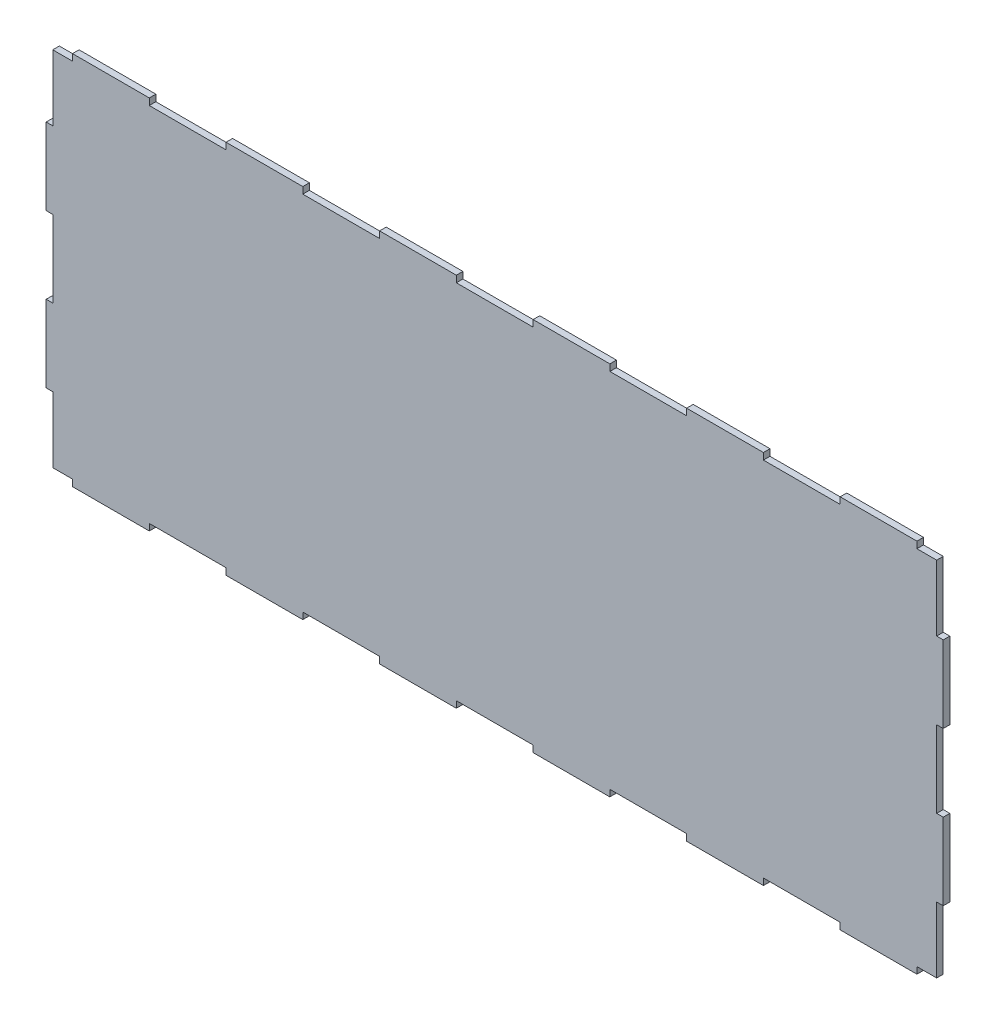
SolidWorks part; units mm, degrees
ref_plane "Front Plane" through (0, 0, 0) normal (0, 0, 1) x (1, 0, 0)
ref_plane "Top Plane" through (0, 0, 0) normal (0, 1, 0) x (1, 0, 0)
ref_plane "Right Plane" through (0, 0, 0) normal (1, 0, 0) x (0, 0, -1)
sketch "Model" plane through (0, 0, 0) normal (0, 0, 1) x (1, 0, 0)
  line L0 (192.5, 85.5) -> (157.5, 85.5)
  line L1 (157.5, 85.5) -> (157.5, 82.5)
  line L2 (157.5, 82.5) -> (122.5, 82.5)
  line L3 (122.5, 82.5) -> (122.5, 85.5)
  line L4 (122.5, 85.5) -> (87.5, 85.5)
  line L5 (87.5, 85.5) -> (87.5, 82.5)
  line L6 (87.5, 82.5) -> (52.5, 82.5)
  line L7 (52.5, 82.5) -> (52.5, 85.5)
  line L8 (52.5, 85.5) -> (17.5, 85.5)
  line L9 (17.5, 85.5) -> (17.5, 82.5)
  line L10 (17.5, 82.5) -> (-17.5, 82.5)
  line L11 (-17.5, 82.5) -> (-17.5, 85.5)
  line L12 (-17.5, 85.5) -> (-52.5, 85.5)
  line L13 (-52.5, 85.5) -> (-52.5, 82.5)
  line L14 (-52.5, 82.5) -> (-87.5, 82.5)
  line L15 (-87.5, 82.5) -> (-87.5, 85.5)
  line L16 (-87.5, 85.5) -> (-122.5, 85.5)
  line L17 (-122.5, 85.5) -> (-122.5, 82.5)
  line L18 (-122.5, 82.5) -> (-157.5, 82.5)
  line L19 (-157.5, 82.5) -> (-157.5, 85.5)
  line L20 (-157.5, 85.5) -> (-192.5, 85.5)
  line L21 (-192.5, 85.5) -> (-192.5, 82.5)
  line L22 (-192.5, 82.5) -> (-201.5, 82.5)
  line L23 (-201.5, 82.5) -> (-201.5, 52.5)
  line L24 (-201.5, 52.5) -> (-204.5, 52.5)
  line L25 (-204.5, 52.5) -> (-204.5, 17.5)
  line L26 (-204.5, 17.5) -> (-201.5, 17.5)
  line L27 (-201.5, 17.5) -> (-201.5, -17.5)
  line L28 (-201.5, -17.5) -> (-204.5, -17.5)
  line L29 (-204.5, -17.5) -> (-204.5, -52.5)
  line L30 (-204.5, -52.5) -> (-201.5, -52.5)
  line L31 (-201.5, -52.5) -> (-201.5, -82.5)
  line L32 (-201.5, -82.5) -> (-192.5, -82.5)
  line L33 (-192.5, -82.5) -> (-192.5, -85.5)
  line L34 (-192.5, -85.5) -> (-157.5, -85.5)
  line L35 (-157.5, -85.5) -> (-157.5, -82.5)
  line L36 (-157.5, -82.5) -> (-122.5, -82.5)
  line L37 (-122.5, -82.5) -> (-122.5, -85.5)
  line L38 (-122.5, -85.5) -> (-87.5, -85.5)
  line L39 (-87.5, -85.5) -> (-87.5, -82.5)
  line L40 (-87.5, -82.5) -> (-52.5, -82.5)
  line L41 (-52.5, -82.5) -> (-52.5, -85.5)
  line L42 (-52.5, -85.5) -> (-17.5, -85.5)
  line L43 (-17.5, -85.5) -> (-17.5, -82.5)
  line L44 (-17.5, -82.5) -> (17.5, -82.5)
  line L45 (17.5, -82.5) -> (17.5, -85.5)
  line L46 (17.5, -85.5) -> (52.5, -85.5)
  line L47 (52.5, -85.5) -> (52.5, -82.5)
  line L48 (52.5, -82.5) -> (87.5, -82.5)
  line L49 (87.5, -82.5) -> (87.5, -85.5)
  line L50 (87.5, -85.5) -> (122.5, -85.5)
  line L51 (122.5, -85.5) -> (122.5, -82.5)
  line L52 (122.5, -82.5) -> (157.5, -82.5)
  line L53 (157.5, -82.5) -> (157.5, -85.5)
  line L54 (157.5, -85.5) -> (192.5, -85.5)
  line L55 (192.5, -85.5) -> (192.5, -82.5)
  line L56 (192.5, -82.5) -> (201.5, -82.5)
  line L57 (201.5, -82.5) -> (201.5, -52.5)
  line L58 (201.5, -52.5) -> (204.5, -52.5)
  line L59 (204.5, -52.5) -> (204.5, -17.5)
  line L60 (204.5, -17.5) -> (201.5, -17.5)
  line L61 (201.5, -17.5) -> (201.5, 17.5)
  line L62 (201.5, 17.5) -> (204.5, 17.5)
  line L63 (204.5, 17.5) -> (204.5, 52.5)
  line L64 (204.5, 52.5) -> (201.5, 52.5)
  line L65 (201.5, 52.5) -> (201.5, 82.5)
  line L66 (201.5, 82.5) -> (192.5, 82.5)
  line L67 (192.5, 82.5) -> (192.5, 85.5)
extrude "Boss-Extrude1" add sketch "Model" along normal blind 3
